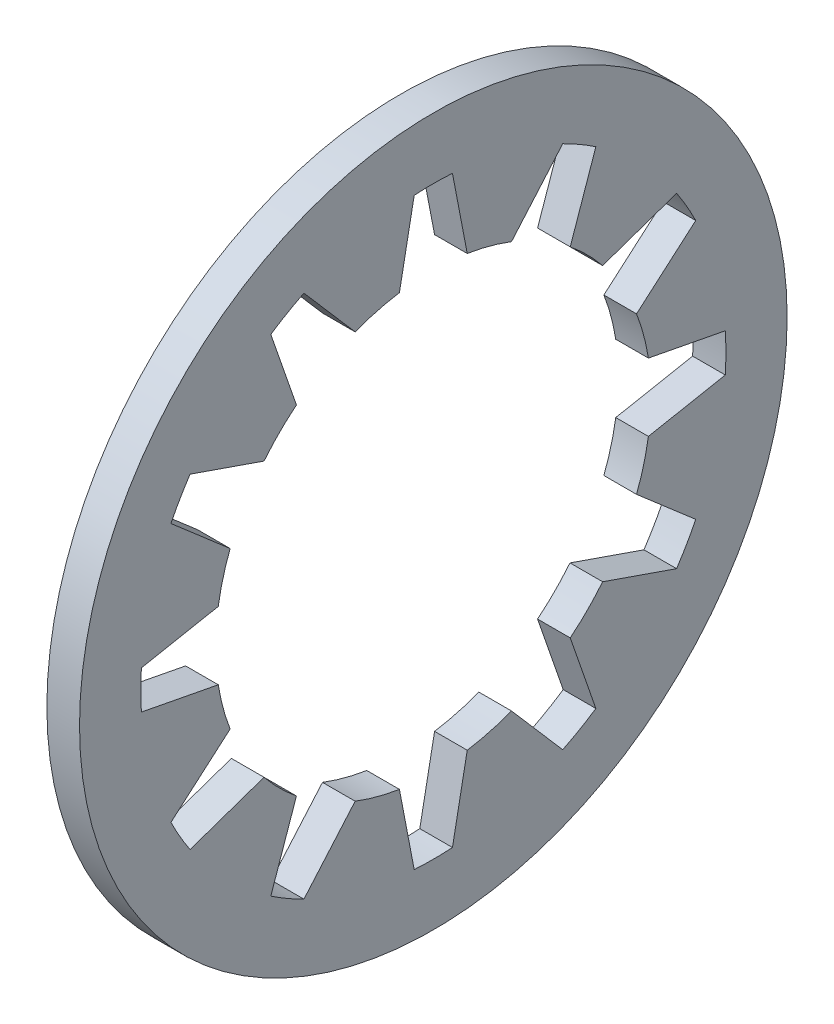
SolidWorks part; units mm, degrees
ref_plane "Plane1" through (0, 0, 0) normal (0, 0, 1) x (1, 0, 0)
ref_plane "Plane2" through (0, 0, 0) normal (0, 1, 0) x (1, 0, 0)
ref_plane "Plane3" through (0, 0, 0) normal (1, 0, 0) x (0, 0, -1)
sketch "SecSke" plane through (0, 0, 0) normal (0, 0, 1) x (1, 0, 0)
  line L0 (-34.925, 0) -> (9.525, 0) construction
  line L1 (0, 8) -> (0, 13)
  line L2 (0, 13) -> (-1.2, 13)
  line L3 (-1.2, 13) -> (-1.2, 8)
  line L4 (-1.2, 8) -> (0, 8)
  dimension "Thickness" = 1.2
  dimension "Inside_dia" = 16
  dimension "Outside_dia" = 26
revolve "Body" add sketch "SecSke" angle 360 about L0
sketch "IntCutSke" plane through (0, 0, 0) normal (1, 0, 0) x (0, 0, -1)
  line L0 (-0.7031, 10.727) -> (-1.3263, 7.4834)
  line L1 (0.7031, 10.727) -> (1.3263, 7.4834)
  line L2 (0, 0) -> (0, 10.75) construction
  arc A0 (1.3263, 7.4834) -> (-1.3263, 7.4834) centre (0, 0) ccw
  arc A1 (0.7031, 10.727) -> (-0.7031, 10.727) centre (0, 0) ccw
  dimension "cut_dia" = 21.5
  dimension "Clr_dia" = 15.2
  dimension "Clr_ang" = 20.1
  dimension "Cut_ang" = 7.5
extrude "IntCut" cut sketch "IntCutSke" against normal through all
pattern_circular "IntCuts" count 12 every 30 about axis through (-34.925, 0, 0) along (1, 0, 0) of "IntCut"
equation "' \"Inside_dia@SecSke\" = 16"
equation "' \"Outside_dia@SecSke\" = 26"
equation "' \"Thickness@SecSke\" = 1.2"
equation "' \"Count@IntCuts\" = 12"
equation "' \"Inside_dia@SecSke\" = 10.5"
equation "' \"Outside_dia@SecSke\" = 18"
equation "' \"Thickness@SecSke\" = 0.9"
equation "' \"Count@IntCuts\" = 9"
equation "' \"Inside_dia@SecSke\" = 6.4"
equation "' \"Outside_dia@SecSke\" = 11"
equation "' \"Thickness@SecSke\" = 0.6"
equation "' \"Inside_dia@SecSke\" = 4.3"
equation "' \"Outside_dia@SecSke\" = 8.5"
equation "' \"Thickness@SecSke\" = 0.45"
equation "' \"Count@IntCuts\" = 8"
equation "\"Angle@IntCuts\" = 360 / \"Count@IntCuts\""
equation "\"Clr_dia@IntCutSke\" =  \"Inside_dia@SecSke\" * 0.95"
equation "\"cut_dia@IntCutSke\" = \"Inside_dia@SecSke\" +  ( \"Outside_dia@SecSke\" - \"Inside_dia@SecSke\" )  * 0.55"
equation "\"Clr_ang@IntCutSke\" = (360 / \"Count@IntCuts\") * 0.67"
equation "\"Cut_ang@IntCutSke\" = (360 / \"Count@IntCuts\") * 0.25"
